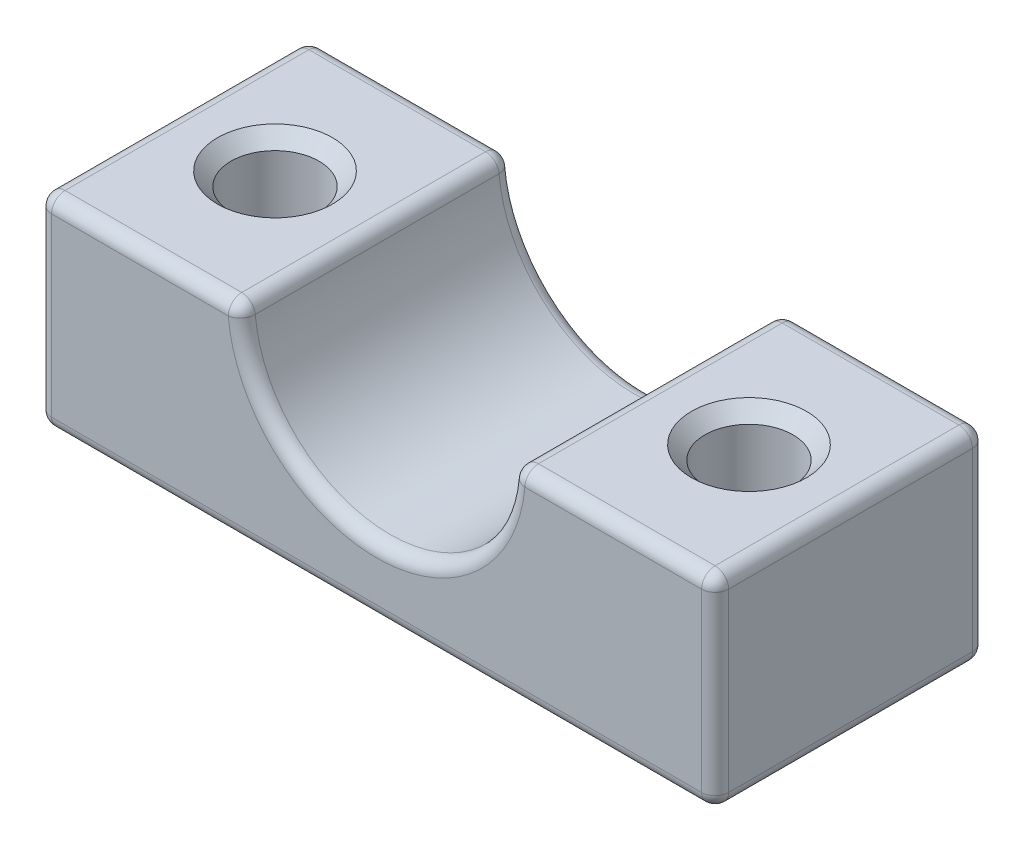
SolidWorks part; units mm, degrees
ref_plane "Płaszczyzna przednia" through (0, 0, 0) normal (0, 0, 1) x (1, 0, 0)
ref_plane "Płaszczyzna górna" through (0, 0, 0) normal (0, 1, 0) x (1, 0, 0)
ref_plane "Płaszczyzna prawa" through (0, 0, 0) normal (1, 0, 0) x (0, 0, -1)
sketch "Szkic1" plane through (0, 0, 0) normal (0, 0, 1) x (1, 0, 0)
  line L0 (-50, 0) -> (50, 0)
  line L1 (-50, -30) -> (50, -30)
  line L2 (-50, -30) -> (-50, 30)
  line L3 (-50, 30) -> (50, 30)
  line L4 (50, -30) -> (50, 30)
  line L5 (-50, -30) -> (50, 30) construction
  line L6 (-50, 30) -> (50, -30) construction
  circle A0 centre (0, 0) radius 20
  point P0 (0, 0)
  dimension "D1" = 40
  dimension "D2" = 30
  dimension "D3" = 100
extrude "Dodanie-wyciągnięcie1" add sketch "Szkic1" along normal blind 40 contours A0 L0 L2 L1 L4
sketch "Szkic2" plane through (0, 0, 0) normal (0, 1, 0) x (1, 0, 0)
  line L0 (-35, 0) -> (-35, -40) construction
  line L1 (-50, 0) -> (-20, 0) construction
  line L2 (-50, -40) -> (-20, -40) construction
  line L3 (35, 0) -> (35, -40) construction
  line L4 (20, 0) -> (50, 0) construction
  line L5 (20, -40) -> (50, -40) construction
  circle A0 centre (-35, -20) radius 6.5
  circle A1 centre (-35, -20) radius 6.5
  circle A2 centre (35, -20) radius 6.5
  circle A3 centre (35, -20) radius 6.5
  dimension "D1" = 13
  dimension "D2" = 20
  dimension "D3" = 20
extrude "Wytnij-wyciągnięcie1" cut sketch "Szkic2" against normal up to next contours A0 | A2
chamfer "Sfazowanie1" distance 2 angle 45 4 edges at (35, -30, 26.5) (35, 0, 26.5) (-35, -30, 26.5) (-35, 0, 26.5)
fillet "Zaokrąglenie1" radius 2 18 edges at (0, -30, 40) (-50, -15, 40) (-50, -30, 20) (-35, 0, 40) (-50, 0, 20) (0, -20, 40) (-20, 0, 20) (20, 0, 20) (35, 0, 40) (50, -30, 20) (50, -15, 40) (50, 0, 20) (-35, 0, 0) (-50, -15, 0) (0, -30, 0) (50, -15, 0) (35, 0, 0) (0, -20, 0)
